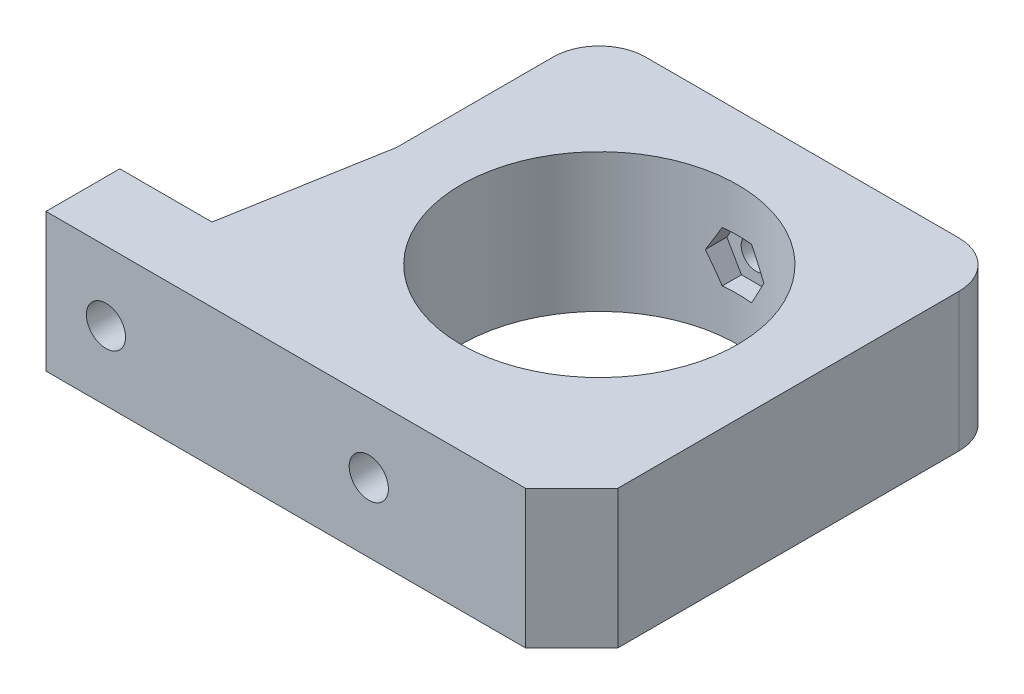
SolidWorks part; units mm, degrees
ref_plane "Alzado" through (0, 0, 0) normal (0, 0, 1) x (1, 0, 0)
ref_plane "Planta" through (0, 0, 0) normal (0, 1, 0) x (1, 0, 0)
ref_plane "Vista lateral" through (0, 0, 0) normal (1, 0, 0) x (0, 0, -1)
sketch "Croquis1" plane through (0, 0, 0) normal (0, 1, 0) x (1, 0, 0)
  line L0 (0, 0) -> (0, -14.5) construction
  line L1 (-35, -25) -> (35, -25)
  line L2 (-35, -25) -> (-35, 0)
  line L3 (-35, 0) -> (35, 0)
  line L4 (35, -25) -> (35, 0)
  line L5 (-35, -17) -> (-25, -17)
  line L6 (-25, -17) -> (-22, 0)
  line L7 (25, -17) -> (22, 0)
  line L8 (35, -17) -> (25, -17)
  circle A0 centre (0, 0) radius 15
  circle A1 centre (0, 0) radius 22
  dimension "D1" = 30
  dimension "D5" = 44
  dimension "D2" = 35
  dimension "D3" = 35
  dimension "D4" = 25
  dimension "D6" = 8
  dimension "D7" = 10
extrude "Saliente-Extruir1" add sketch "Croquis1" along normal blind 15 contours L0 A0 L3 A1 | L0 A1 L3 A0 | A1 L0 A0 L3 | A0 L0 A1 L3 | A1 L0 L1 L4 L8 L7 | L0 A1 L6 L5 L2 L1
sketch "Croquis2" plane through (0, 0, 25) normal (0, 0, 1) x (1, 0, 0)
  line L0 (-25, 15) -> (-25, 0) construction
  line L1 (0, 0) -> (0, 15) construction
  circle A0 centre (-28.5, 7.5) radius 2.125
  circle A1 centre (28.5, 7.5) radius 2.125
  circle A2 centre (0, 7.5) radius 2.125
  dimension "D2" = 4.25
  dimension "D1" = 3.5
  dimension "D3" = 57
extrude "Cortar-Extruir1" cut sketch "Croquis2" against normal up to next
sketch "Croquis3" plane through (0, 0, 17) normal (0, 0, -1) x (-1, 0, 0)
  line L1 (25, 5.4793) -> (28.5, 3.4585)
  line L2 (28.5, 3.4585) -> (32, 5.4793)
  line L3 (32, 5.4793) -> (32, 9.5207)
  line L4 (32, 9.5207) -> (28.5, 11.5415)
  line L5 (28.5, 11.5415) -> (25, 9.5207)
  line L6 (25, 9.5207) -> (25, 5.4793)
  line L7 (-25, 5.4793) -> (-25, 9.5207)
  line L8 (-25, 9.5207) -> (-28.5, 11.5415)
  line L9 (-28.5, 11.5415) -> (-32, 9.5207)
  line L10 (-32, 9.5207) -> (-32, 5.4793)
  line L11 (-32, 5.4793) -> (-28.5, 3.4585)
  line L12 (-28.5, 3.4585) -> (-25, 5.4793)
  circle A0 centre (28.5, 7.5) radius 3.5 construction
  circle A1 centre (-28.5, 7.5) radius 3.5 construction
  dimension "D1" = 7
  dimension "D2" = 7
extrude "Cortar-Extruir2" cut sketch "Croquis3" against normal blind 3
sketch "Sketch1" plane through (0, 15, 0) normal (0, 1, 0) x (1, 0, 0)
  line L0 (22, -20) -> (17, -25)
  line L1 (22, 0) -> (35, 0)
  line L2 (22, 0) -> (22, -25)
  line L3 (22, -25) -> (35, -25)
  line L4 (35, 0) -> (35, -25)
  line L5 (-35, -25) -> (35, -25) construction
  line L6 (17, -25) -> (22, -25)
  line M5 (25, -17) -> (22, 0)
  line M10 (-35, -25) -> (35, -25)
  line M11 (35, -25) -> (35, -17)
  line M12 (35, -17) -> (25, -17)
  dimension "D1" = 5
  dimension "D2" = 45
extrude "Cut-Extrude1" cut sketch "Sketch1" against normal through all contours L2 L0 M10 | L2 M5 M10 M11 M12
sketch "Sketch2" plane through (0, 0, 25) normal (0, 0, 1) x (1, 0, 0)
  line L1 (2.0207, 4) -> (4.0415, 7.5)
  line L2 (4.0415, 7.5) -> (2.0207, 11)
  line L3 (2.0207, 11) -> (-2.0207, 11)
  line L4 (-2.0207, 11) -> (-4.0415, 7.5)
  line L5 (-4.0415, 7.5) -> (-2.0207, 4)
  line L6 (-2.0207, 4) -> (2.0207, 4)
  circle A0 centre (0, 7.5) radius 3.5 construction
  dimension "D1" = 7
extrude "Cut-Extrude2" cut sketch "Sketch2" against normal up to next from offset 4 offset against normal yes
sketch "Sketch3" plane through (0, 0, 25) normal (0, 0, 1) x (1, 0, 0)
  line L1 (1.5877, 4.75) -> (3.1754, 7.5)
  line L2 (3.1754, 7.5) -> (1.5877, 10.25)
  line L3 (1.5877, 10.25) -> (-1.5877, 10.25)
  line L4 (-1.5877, 10.25) -> (-3.1754, 7.5)
  line L5 (-3.1754, 7.5) -> (-1.5877, 4.75)
  line L6 (-1.5877, 4.75) -> (1.5877, 4.75)
  circle A0 centre (0, 7.5) radius 2.75 construction
  dimension "D1" = 5.5
extrude "Cut-Extrude3" cut sketch "Sketch3" against normal blind 3 from offset 39 offset against normal yes
sketch "Sketch5" plane through (0, 15, 0) normal (0, 1, 0) x (1, 0, 0)
  line L1 (-22, 0) -> (22, 0)
  line L2 (-22, 0) -> (-22, 22)
  line L3 (-22, 22) -> (22, 22)
  line L4 (22, 0) -> (22, 22)
  circle A0 centre (-17, 17) radius 5
  circle A1 centre (17, 17) radius 5
  circle A2 centre (0, 0) radius 15
  circle A3 centre (0, 0) radius 15 construction
  arc M3 (22, 0) -> (-22, 0) centre (0, 0) ccw
  dimension "D1" = 10
  dimension "D2" = 5
  dimension "D3" = 5
  dimension "D4" = 5
extrude "Boss-Extrude3" add sketch "Sketch5" against normal up to surface (15 mm away) contours A0 L3 M3 | A1 L3 M3 | A1 M3 | A1 L4 M3 | A0 M3 | A0 L2 M3 up to face at (-8, 0, 11.7143)
sketch "Sketch4" plane through (0, 0, 25) normal (0, 0, 1) x (1, 0, 0)
  circle A0 centre (0, 7.5) radius 1.625
  dimension "D1" = 3.25
extrude "Cut-Extrude4" cut sketch "Sketch4" against normal through all from offset 20 offset against normal yes
